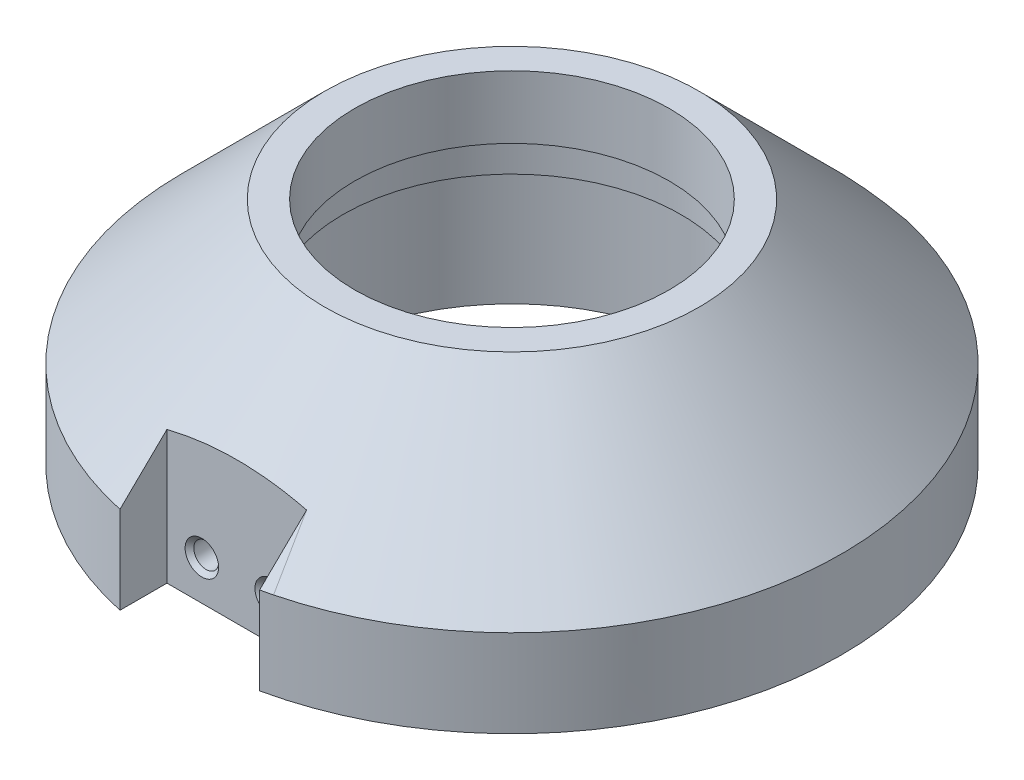
SolidWorks part; units mm, degrees
material "Chrome Stainless Steel"
ref_plane "Front Plane" through (0, 0, 0) normal (0, 0, 1) x (1, 0, 0)
ref_plane "Top Plane" through (0, 0, 0) normal (0, 1, 0) x (1, 0, 0)
ref_plane "Right Plane" through (0, 0, 0) normal (1, 0, 0) x (0, 0, -1)
sketch "Sketch1" plane through (0, 0, 0) normal (0, 0, 1) x (1, 0, 0)
  line L0 (0, 0) -> (29.972, 0)
  line L1 (29.972, 0) -> (29.972, 2.54)
  line L2 (29.972, 2.54) -> (17.018, 15.494)
  line L3 (19.812, 12.7) -> (0, 12.7) construction
  line L4 (0, 12.7) -> (0, 0)
  line L5 (0, 12.7) -> (0, 15.494)
  line L6 (0, 15.494) -> (17.018, 15.494)
  dimension "D1" = 45
  dimension "D2" = 29.972
  dimension "D3" = 12.7
  dimension "D4" = 2.54
  dimension "D5" = 15.494
revolve "Revolve1" add sketch "Sketch1" angle 360 about L4
ref_plane "Plane1" through (0, 0, 29.972) normal (0, 0, 1) x (1, 0, 0)
sketch "Sketch4" plane through (0, 15.494, 0) normal (0, 1, 0) x (1, 0, 0)
  line L0 (0, 0) -> (0, -23.9522)
  line L1 (0, -23.9522) -> (11.8011, -23.9522)
  dimension "D1" = 23.9522
ref_plane "Plane3" through (0, 0, 23.9522) normal (0, 0, 1) x (1, 0, 0)
sketch "Sketch14" plane through (0, 0, 0) normal (0, -1, 0) x (1, 0, 0)
  circle A0 centre (0, 0) radius 29.972
  circle A1 centre (0, 0) radius 29.972 construction
extrude "Boss-Extrude1" add sketch "Sketch14" along normal blind 5.4102
ref_plane "Plane4" through (0, 0, -29.972) normal (0, 0, -1) x (-1, 0, 0)
sketch "Sketch15" plane through (0, -5.4102, 0) normal (0, -1, 0) x (1, 0, 0)
  line L0 (0, 29.972) -> (0, 25.019) construction
  line L1 (-6.35, 25.019) -> (6.35, 25.019)
  line L2 (6.35, 25.019) -> (6.35, 29.972)
  line L3 (6.35, 29.972) -> (-6.35, 29.972)
  line L4 (-6.35, 25.019) -> (-6.35, 29.972)
  circle A0 centre (0, 0) radius 29.972 construction
  dimension "D1" = 4.953
  dimension "D2" = 12.7
extrude "Cut-Extrude2" cut sketch "Sketch15" against normal through all
sketch "Sketch17" plane through (0, 0, 25.019) normal (0, 0, 1) x (1, 0, 0)
  line L1 (-6.35, -1.8161) -> (6.35, -1.8161)
  line L2 (-6.35, 6.6997) -> (-6.35, -5.4102) construction
  line L3 (-6.35, 2.54) -> (-6.35, -5.4102)
  point P6 (-3.175, -1.8161)
  point P7 (3.175, -1.8161)
  point P8 (-6.35, 0.6448)
  point P13 (-6.35, -1.4351)
  dimension "D1" = 0.381
  dimension "D2" = 6.35
  dimension "D3" = 3.175
hole_wizard "#4-40 Tapped Hole1" positions "Sketch19" profile "Sketch18" tap size "#4-40" standard "ANSI Inch"
sketch "Sketch19" plane through (0, 0, 25.019) normal (0, 0, 1) x (1, 0, 0)
  point P0 (3.175, -1.8161)
  point P3 (-3.175, -1.8161)
cosmetic thread "Hole Thread1" parameters "D1"=5.6896, "D2"=2.8448
cosmetic thread "Hole Thread2" parameters "D1"=5.6896, "D2"=2.8448
sketch "Sketch18" plane through (3.175, -1.8161, 25.019) normal (1, 0, 0) x (0, -1, 0)
  line L0 (0, 0) -> (0, 8.2992)
  line L1 (0, 8.2992) -> (1.1303, 7.62)
  line L2 (1.1303, 7.62) -> (1.1303, 0.3937)
  line L3 (1.1303, 0.3937) -> (1.524, 0)
  line L5 (1.524, 0) -> (0, 0)
  line L6 (-1.1303, 0.3937) -> (-1.524, 0) construction
  line L10 (0, 8.2992) -> (-1.1303, 7.62) construction
  line L11 (0, -6.35) -> (0, 107.95) construction
  dimension "Tap Drill Dia." = 2.2606
  dimension "Tap Drill Depth" = 7.62
  dimension "Near C'Sink Dia." = 3.048
  dimension "Near C'Sink Angle" = 90
  dimension "Drill Angle" = 118
ref_plane "Plane5" through (0, 0, -29.972) normal (0, 0, -1) x (-1, 0, 0)
sketch "Sketch20" plane through (0, 0, -29.972) normal (0, 0, -1) x (-1, 0, 0)
  line L0 (0, 2.54) -> (0, -5.4102) construction
  line L1 (-29.972, 2.54) -> (29.972, 2.54) construction
  line L2 (-29.972, -5.4102) -> (29.972, -5.4102) construction
  line L3 (-6.604, -5.4102) -> (6.604, -5.4102)
  line L4 (6.604, -5.4102) -> (6.604, 2.54)
  line L5 (6.604, 2.54) -> (-6.604, 2.54) construction
  line L6 (-6.604, -5.4102) -> (-6.604, 2.54)
  line L7 (-6.604, 2.54) -> (-6.604, 6.7594)
  line L8 (-6.604, 6.7594) -> (6.604, 6.7594)
  line L9 (6.604, 6.7594) -> (6.604, 2.54)
  point P6 (0, -1.4351)
  dimension "D1" = 13.208
extrude "Cut-Extrude3" cut sketch "Sketch20" against normal blind 0.762
sketch "Sketch21" plane through (0, 0, -29.21) normal (0, 0, -1) x (-1, 0, 0)
  line L0 (0, 3.302) -> (0, -5.4102) construction
  line L3 (-6.604, -5.4102) -> (6.604, -5.4102) construction
  spline S0 degree 3 poles (6.604, 2.5648) (6.0632, 2.684) (5.5181, 2.7903) (4.4183, 2.9747) (3.8653, 3.0525) (2.2096, 3.2391) (1.1052, 3.302) (-1.1048, 3.302) (-2.2104, 3.2391) (-3.8697, 3.0519) (-4.424, 2.9738) (-5.5206, 2.7898) (-6.0644, 2.6838) (-6.604, 2.5648) knots 0 0 0 0 0.125 0.125 0.25 0.25 0.5 0.5 0.75 0.75 0.875 0.875 1 1 1 1 construction
  point P6 (3.175, -1.4414)
  point P7 (-3.175, -1.4415)
  dimension "D1" = 6.35
  dimension "D2" = 3.9688
hole_wizard "#4-40 Tapped Hole2" positions "Sketch23" profile "Sketch22" tap size "#4-40" standard "ANSI Inch"
sketch "Sketch23" plane through (0, 0, -29.21) normal (0, 0, -1) x (-1, 0, 0)
  point P0 (-3.175, -1.4415)
  point P3 (3.175, -1.4414)
sketch "Sketch22" plane through (3.175, -1.4415, -29.21) normal (1, 0, 0) x (0, 1, 0)
  line L0 (0, 0) -> (0, 8.2992)
  line L1 (0, 8.2992) -> (1.1303, 7.62)
  line L2 (1.1303, 7.62) -> (1.1303, 0.3937)
  line L3 (1.1303, 0.3937) -> (1.524, 0)
  line L5 (1.524, 0) -> (0, 0)
  line L6 (-1.1303, 0.3937) -> (-1.524, 0) construction
  line L10 (0, 8.2992) -> (-1.1303, 7.62) construction
  line L11 (0, -6.35) -> (0, 107.95) construction
  dimension "Tap Drill Dia." = 2.2606
  dimension "Tap Drill Depth" = 7.62
  dimension "Near C'Sink Dia." = 3.048
  dimension "Near C'Sink Angle" = 90
  dimension "Drill Angle" = 118
cosmetic thread "Hole Thread3" parameters "D1"=5.6896, "D2"=2.8448
cosmetic thread "Hole Thread4" parameters "D1"=5.6896, "D2"=2.8448
sketch "Sketch24" plane through (0, -5.4102, 0) normal (0, -1, 0) x (1, 0, 0)
  circle A0 centre (0, 0) radius 14.3002
  dimension "D1" = 28.6004
extrude "Cut-Extrude4" cut sketch "Sketch24" against normal through all
sketch "Sketch25" plane through (0, -5.4102, 0) normal (0, -1, 0) x (1, 0, 0)
  circle A0 centre (0, 0) radius 15.367
  dimension "D1" = 30.734
ref_plane "Plane6" through (0, 9.779, 0) normal (0, 1, 0) x (1, 0, 0)
extrude "Cut-Extrude5" cut sketch "Sketch25" against normal up to surface (15.1892 mm away)
sketch "Sketch26" plane through (0, -5.4102, 0) normal (0, -1, 0) x (1, 0, 0)
  circle A0 centre (0, 0) radius 17.907
  dimension "D1" = 35.814
extrude "Cut-Extrude6" cut sketch "Sketch26" against normal offset from surface (12.0142 mm away) 3.175 up to face at (-15.367, 9.779, 0)
sketch "Sketch27" plane through (0, 6.604, 0) normal (0, -1, 0) x (1, 0, 0)
  line L1 (-11.557, 11.557) -> (11.557, 11.557)
  line L2 (-11.557, 11.557) -> (-11.557, -11.557)
  line L3 (-11.557, -11.557) -> (11.557, -11.557)
  line L4 (11.557, 11.557) -> (11.557, -11.557)
  line L5 (-11.557, 11.557) -> (11.557, -11.557) construction
  line L6 (-11.557, -11.557) -> (11.557, 11.557) construction
  point P0 (0, 0)
  dimension "D1" = 23.114
hole_wizard "#0-80 Tapped Hole1" positions "Sketch31" profile "Sketch30" tap size "#0-80" standard "ANSI Inch"
sketch "Sketch31" plane through (0, 6.604, 0) normal (0, -1, 0) x (-1, 0, 0)
  point P0 (11.557, -11.557)
  point P3 (-11.557, -11.557)
  point P6 (-11.557, 11.557)
  point P9 (11.557, 11.557)
sketch "Sketch30" plane through (-11.557, 6.604, 11.557) normal (1, 0, 0) x (0, 0, -1)
  line L0 (0, 0) -> (0, 7.9779)
  line L1 (0, 7.9779) -> (0.5956, 7.62)
  line L2 (0.5956, 7.62) -> (0.5956, 0)
  line L5 (0.5956, 0) -> (0, 0)
  line L10 (0, 7.9779) -> (-0.5956, 7.62) construction
  line L11 (0, -6.35) -> (0, 107.95) construction
  dimension "Tap Drill Dia." = 1.1913
  dimension "Tap Drill Depth" = 7.62
  dimension "Drill Angle" = 118
cosmetic thread "Hole Thread5" parameters "D1"=3.302, "D2"=1.524
cosmetic thread "Hole Thread6" parameters "D1"=3.302, "D2"=1.524
cosmetic thread "Hole Thread7" parameters "D1"=3.302, "D2"=1.524
cosmetic thread "Hole Thread8" parameters "D1"=3.302, "D2"=1.524
